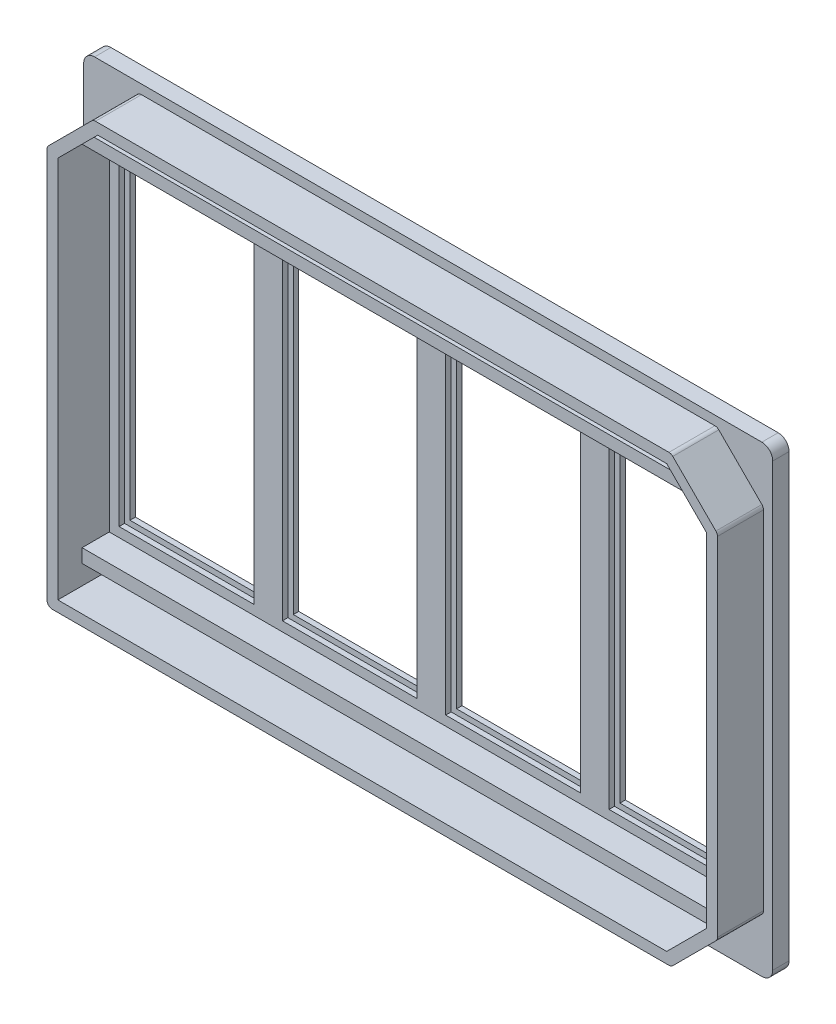
SolidWorks part; units mm, degrees
ref_plane "Front Plane" through (0, 0, 0) normal (0, 0, 1) x (1, 0, 0)
ref_plane "Top Plane" through (0, 0, 0) normal (0, 1, 0) x (1, 0, 0)
ref_plane "Right Plane" through (0, 0, 0) normal (1, 0, 0) x (0, 0, -1)
sketch "Sketch1" plane through (0, 0, 0) normal (0, 0, 1) x (1, 0, 0)
  line L1 (0, 0) -> (126.56, 0)
  line L2 (0, 0) -> (0, 85)
  line L3 (0, 85) -> (126.56, 85)
  line L4 (126.56, 0) -> (126.56, 85)
  dimension "D1" = 126.56
  dimension "D2" = 85
extrude "Boss-Extrude1" add sketch "Sketch1" along normal blind 3
sketch "Sketch2" plane through (0, 0, 3) normal (0, 0, 1) x (1, 0, 0)
  line L0 (126.56, 85) -> (0, 85) construction
  line L1 (1.7, 83.3) -> (124.86, 83.3)
  line L2 (1.7, 83.3) -> (1.7, 1.7)
  line L3 (1.7, 1.7) -> (124.86, 1.7)
  line L4 (124.86, 83.3) -> (124.86, 1.7)
  line L5 (126.56, 0) -> (126.56, 85) construction
  line L6 (0, 0) -> (126.56, 0) construction
  line L7 (0, 85) -> (0, 0) construction
  point P12 (0, 42.5)
  dimension "D1" = 1.7
  dimension "D2" = 1.7
  dimension "D3" = 1.7
  dimension "D4" = 1.7
extrude "Boss-Extrude2" add sketch "Sketch2" along normal blind 8.45
sketch "Sketch3" plane through (0, 0, 11.45) normal (0, 0, 1) x (1, 0, 0)
  line L0 (1.7, 83.3) -> (1.7, 74.8)
  line L1 (1.7, 83.3) -> (1.7, 1.7) construction
  line L2 (1.7, 83.3) -> (10.2, 83.3)
  line L3 (124.86, 83.3) -> (1.7, 83.3) construction
  line L4 (10.2, 83.3) -> (1.7, 74.8)
  line L5 (124.86, 83.3) -> (116.36, 83.3)
  line L6 (124.86, 83.3) -> (124.86, 74.8)
  line L7 (124.86, 1.7) -> (124.86, 83.3) construction
  line L8 (116.36, 83.3) -> (124.86, 74.8)
  line L9 (124.86, 1.7) -> (124.86, 10.2)
  line L11 (124.86, 1.7) -> (116.36, 1.7)
  line L12 (1.7, 1.7) -> (124.86, 1.7) construction
  line L13 (116.36, 1.7) -> (124.86, 10.2)
  dimension "D1" = 8.5
  dimension "D2" = 8.5
  dimension "D3" = 8.5
  dimension "D4" = 8.5
  dimension "D5" = 8.5
  dimension "D6" = 8.5
extrude "Cut-Extrude1" cut sketch "Sketch3" against normal blind 8.45
fillet "Fillet1" radius 1 7 edges at (1.7, 1.7, 7.225) (116.36, 83.3, 7.225) (124.86, 74.8, 7.225) (1.7, 74.8, 7.225) (10.2, 83.3, 7.225) (116.36, 1.7, 7.225) (124.86, 10.2, 7.225)
shell "Shell1" thickness 2
fillet "Fillet2" radius 2 4 edges at (0, 0, 1.5) (126.56, 0, 1.5) (126.56, 85, 1.5) (0, 85, 1.5)
sketch "Sketch4" plane through (0, 0, 2) normal (0, 0, 1) x (1, 0, 0)
  line L1 (5.5, 72.3) -> (30.25, 72.3)
  line L2 (5.5, 72.3) -> (5.5, 11.55)
  line L3 (5.5, 11.55) -> (30.25, 11.55)
  line L4 (30.25, 72.3) -> (30.25, 11.55)
  line L6 (35.5, 72.3) -> (60.25, 72.3)
  line L7 (35.5, 72.3) -> (35.5, 11.55)
  line L8 (35.5, 11.55) -> (60.25, 11.55)
  line L9 (60.25, 72.3) -> (60.25, 11.55)
  line L10 (65.5, 72.3) -> (90.25, 72.3)
  line L11 (65.5, 72.3) -> (65.5, 11.55)
  line L12 (65.5, 11.55) -> (90.25, 11.55)
  line L13 (90.25, 72.3) -> (90.25, 11.55)
  line L14 (95.5, 72.3) -> (120.25, 72.3)
  line L15 (95.5, 72.3) -> (95.5, 11.55)
  line L16 (95.5, 11.55) -> (120.25, 11.55)
  line L17 (120.25, 72.3) -> (120.25, 11.55)
  line L18 (3.7, 73.9716) -> (3.7, 3.7) construction
  dimension "D1" = 4
  dimension "D2" = 60.75
  dimension "D3" = 1.8
  dimension "D4" = 9
extrude "Cut-Extrude2" cut sketch "Sketch4" against normal blind 1
sketch "Sketch5" plane through (0, 0, 1) normal (0, 0, 1) x (1, 0, 0)
  line L0 (30.25, 72.3) -> (5.5, 72.3) construction
  line L1 (6.5, 71.3) -> (29.25, 71.3)
  line L2 (6.5, 71.3) -> (6.5, 12.55)
  line L3 (6.5, 12.55) -> (29.25, 12.55)
  line L4 (29.25, 71.3) -> (29.25, 12.55)
  line L5 (30.25, 11.55) -> (30.25, 72.3) construction
  line L6 (5.5, 72.3) -> (5.5, 11.55) construction
  line L7 (5.5, 11.55) -> (30.25, 11.55) construction
  line L8 (36.5, 71.3) -> (59.25, 71.3)
  line L9 (36.5, 71.3) -> (36.5, 12.55)
  line L10 (36.5, 12.55) -> (59.25, 12.55)
  line L11 (59.25, 71.3) -> (59.25, 12.55)
  line L12 (66.5, 71.3) -> (89.25, 71.3)
  line L13 (66.5, 71.3) -> (66.5, 12.55)
  line L14 (66.5, 12.55) -> (89.25, 12.55)
  line L15 (89.25, 71.3) -> (89.25, 12.55)
  line L16 (96.5, 71.3) -> (119.25, 71.3)
  line L17 (96.5, 71.3) -> (96.5, 12.55)
  line L18 (96.5, 12.55) -> (119.25, 12.55)
  line L19 (119.25, 71.3) -> (119.25, 12.55)
  dimension "D1" = 1
  dimension "D2" = 1
  dimension "D3" = 1
  dimension "D4" = 1
  dimension "D5" = 4
extrude "Cut-Extrude3" cut sketch "Sketch5" against normal blind 1
sketch "Sketch7" plane through (0, 0, 2) normal (0, 0, 1) x (1, 0, 0)
  line L0 (3.7, 73.9716) -> (122.86, 73.9716)
  line L1 (122.86, 73.9716) -> (120.6554, 76.1762)
  line L2 (122.86, 73.9716) -> (115.5316, 81.3) construction
  line L6 (120.6554, 76.1762) -> (5.9046, 76.1762)
  line L7 (11.0284, 81.3) -> (3.7, 73.9716) construction
  line L8 (5.9046, 76.1762) -> (3.7, 73.9716)
  line L9 (3.7, 9.7823) -> (3.7, 7.2823)
  line L10 (3.7, 73.9716) -> (3.7, 3.7) construction
  line L11 (3.7, 7.2823) -> (119.1958, 7.3642)
  line L12 (115.5316, 3.7) -> (122.86, 11.0284) construction
  line L13 (3.7, 9.7823) -> (121.6138, 9.7823)
  line L14 (121.6138, 9.7823) -> (119.1958, 7.3642)
  dimension "D1" = 2.5
extrude "Boss-Extrude4" add sketch "Sketch7" along normal blind 5
